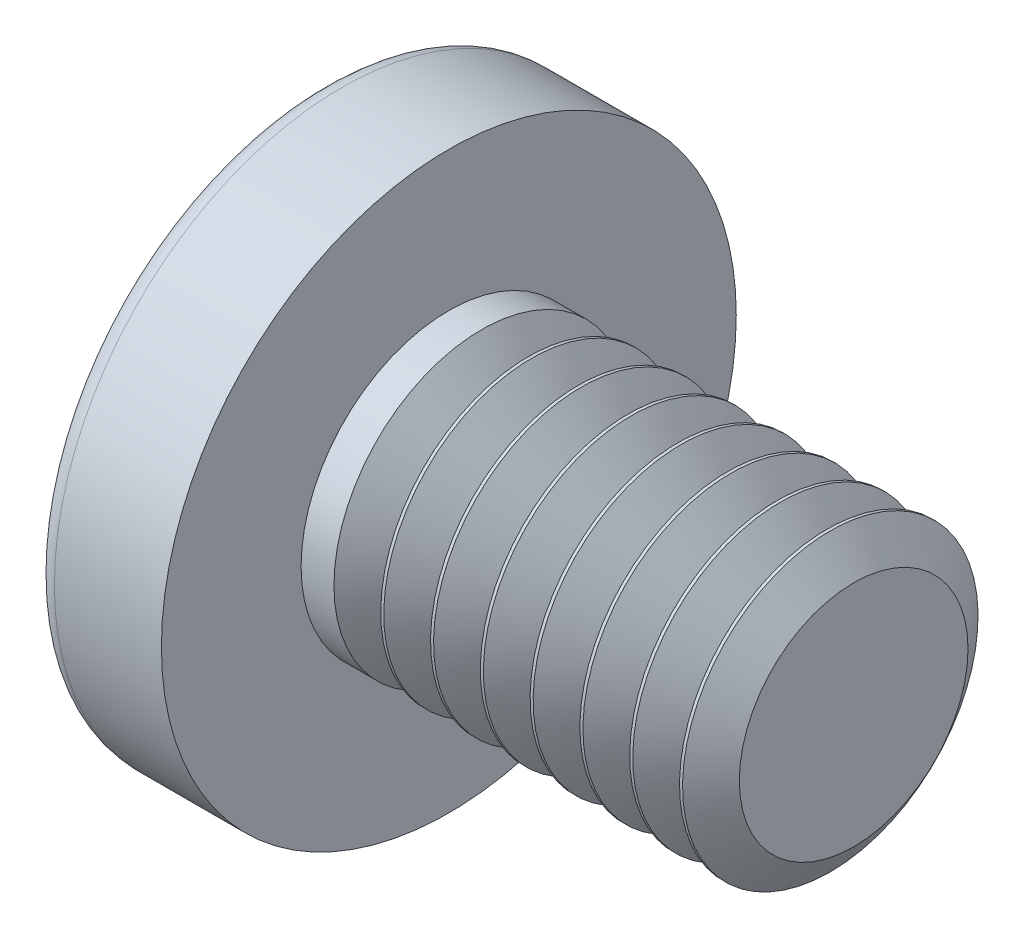
SolidWorks part; units mm, degrees
ref_plane "Plane1" through (0, 0, 0) normal (0, 0, 1) x (1, 0, 0)
ref_plane "Plane2" through (0, 0, 0) normal (0, 1, 0) x (1, 0, 0)
ref_plane "Plane3" through (0, 0, 0) normal (1, 0, 0) x (0, 0, -1)
other "Configuration Table"
sketch "BodySke" plane through (0, 0, 0) normal (0, 0, 1) x (1, 0, 0)
  line L0 (1.3462, 0.9271) -> (1.3462, 1.8034)
  line L1 (1.5227, 6.35) -> (1.5227, -3.175) construction
  line L2 (-25.4, 0) -> (127, 0) construction
  line L3 (3.8862, 0) -> (0, 0)
  line L4 (1.3462, 0.9271) -> (3.8862, 0.9271)
  line L5 (3.8862, 0.9271) -> (3.8862, 0)
  line L6 (0.6746, 1.8034) -> (1.3462, 1.8034)
  line L7 (1.3462, -0.9271) -> (3.8862, -0.9271) construction
  line L8 (0.7112, 6.35) -> (0.7112, -3.175) construction
  arc A0 (0.5721, 1.7514) -> (0, 0) centre (2.9667, 0) ccw
  arc A2 (0.5721, 1.7514) -> (0.6746, 1.8034) centre (0.6746, 1.6764) cw
  dimension "Head_crown_rad" = 2.9667
  dimension "Head_fillet_rad" = 0.127
  dimension "Diameter" = 1.8542
  dimension "Length" = 2.54
  dimension "Head_ht" = 1.3462
  dimension "Head_dia" = 3.6068
  dimension "Advance" = 0.3531
  dimension "Thread_nom" = 3.175
revolve "Base-Revolve" add sketch "BodySke" angle 360 about L2
cosmetic thread "ThreadCosmetic" [suppressed] parameters "Thread_length"=2.1869, "Thread_minor"=1.4351
sketch "Sketch3" plane through (0, 0, 0) normal (1, 0, 0) x (0, 0, -1)
  line L0 (0.3048, -1.1303) -> (-0.3048, -1.1303)
  line L1 (0.3048, -1.1303) -> (0.3048, 1.1303)
  line L2 (-0.3048, 1.1303) -> (0.3048, 1.1303)
  line L3 (-0.3048, 1.1303) -> (-0.3048, -1.1303)
  dimension "Cross_dia" = 2.2606
  dimension "D1" = 1.1303
  dimension "Cross_width" = 0.6096
  dimension "D2" = 0.3048
ref_plane "Plane4" through (1.1684, 0, 0) normal (1, 0, 0) x (0, 0, -1)
sketch "Sketch4" plane through (1.1684, 0, 0) normal (1, 0, 0) x (0, 0, -1)
  line L0 (0.1524, -0.1524) -> (-0.1524, -0.1524)
  line L1 (0.1524, -0.1524) -> (0.1524, 0.1524)
  line L2 (-0.1524, 0.1524) -> (0.1524, 0.1524)
  line L3 (-0.1524, 0.1524) -> (-0.1524, -0.1524)
  dimension "D2" = 0.3048
  dimension "D1" = 0.3048
  dimension "D3" = 0.1524
  dimension "D4" = 0.1524
loft "Cut-Loft1" cut profiles "Sketch3", "Sketch4"
pattern_circular "CirPattern1" count 2 every 90 about axis through (0, 0, 0) along (1, 0, 0) of "Cut-Loft1"
sketch "ThdSchSke" plane through (0, 0, 0) normal (0, 0, 1) x (1, 0, 0)
  line L0 (1.6993, -0.7175) -> (1.5525, -0.9271)
  line L1 (1.6993, -0.7175) -> (1.846, -0.9271)
  line L2 (1.846, -0.9271) -> (1.846, -1.1589)
  line L3 (-3.175, 0) -> (5.1513, 0) construction
  line L5 (1.846, -1.1589) -> (1.5525, -1.1589)
  line L6 (1.5525, -1.1589) -> (1.5525, -0.9271)
  dimension "Diameter" = 1.8542
  dimension "SideAngle" = 55
  dimension "VeeAngle" = 70
  dimension "Thread_minor" = 1.4351
  dimension "Overcut" = 2.3177
  dimension "Start" = 1.6993
revolve "ThreadSchematic" cut sketch "ThdSchSke" angle 360 about L3
pattern_linear "ThdSchPat" count 8 spacing 0.3124 along (1, 0, 0) of "ThreadSchematic"
equation "\"D1@Sketch3\" = \"Cross_dia@Sketch3\" / 2"
equation "\"D2@Sketch3\" = \"Cross_width@Sketch3\" / 2"
equation "\"D1@Sketch4\" = \"Cross_width@Sketch3\" *.5"
equation "\"D2@Sketch4\" = \"D1@Sketch4\""
equation "\"D3@Sketch4\" = \"D1@Sketch4\" / 2"
equation "\"D4@Sketch4\" = \"D2@Sketch4\" / 2"
equation "\"Thread_length@ThreadCosmetic\" = ((sgn( (\"Length@BodySke\" - \"Advance@BodySke\" ) - \"Thread_nom@BodySke\" )-1)*( (\"Length@BodySke\" - \"Advance@BodySke\" ) - \"Thread_nom@BodySke\" ))/-2+ \"Thread_nom@BodySke\""
equation "\"Thread_minor@ThdSchSke\" = \"Thread_minor@ThreadCosmetic\""
equation "\"Diameter@ThdSchSke\" = \"Diameter@BodySke\""
equation "\"Overcut@ThdSchSke\" = \"Diameter@BodySke\" * 1.25"
equation "\"Start@ThdSchSke\" = \"Head_ht@BodySke\" + \"Length@BodySke\" - \"Thread_length@ThreadCosmetic\"  '---Non-countersunk---"
equation "\"Num_threads@ThdSchPat\" = int( \"Thread_length@ThreadCosmetic\" / \"Advance@BodySke\" + 0.999 )  + 1"
equation "\"Advance@ThdSchPat\" = \"Thread_length@ThreadCosmetic\" /  (\"Num_threads@ThdSchPat\" - 1) 'relax it"
